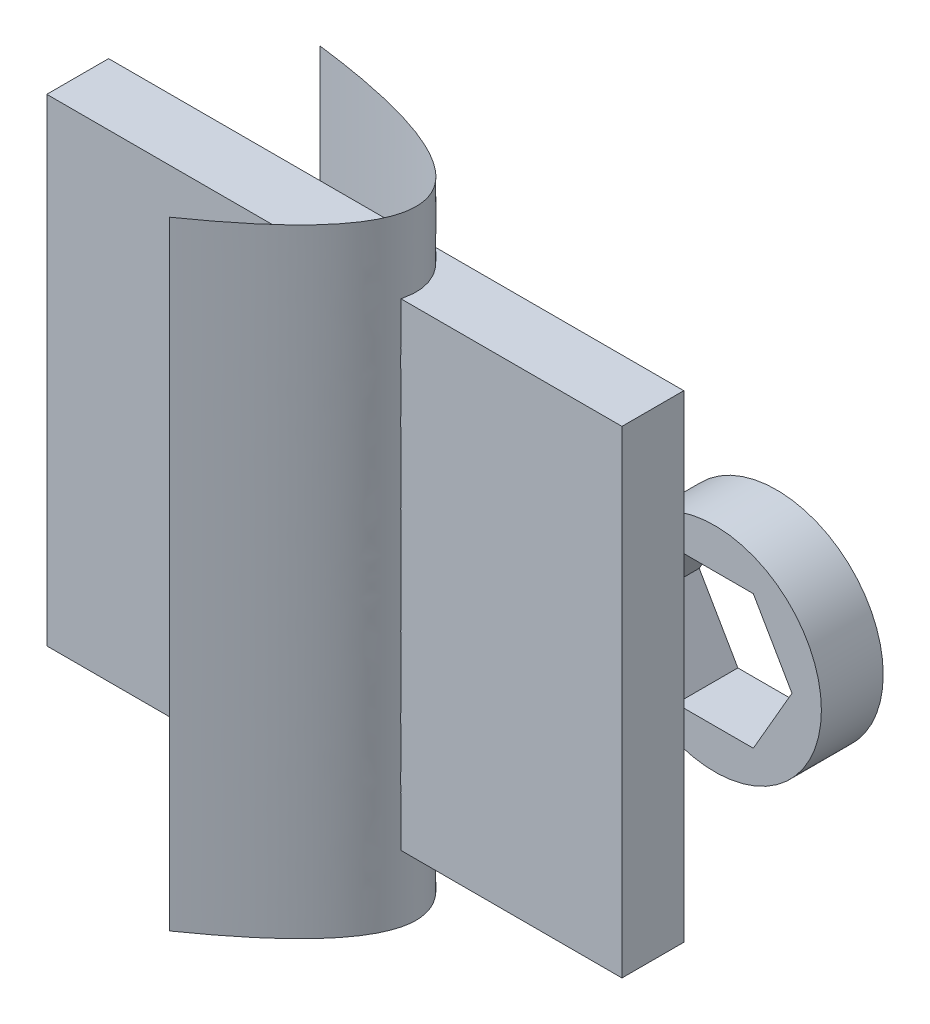
SolidWorks part; units mm, degrees
ref_plane "Спереди" through (0, 0, 0) normal (0, 0, 1) x (1, 0, 0)
ref_plane "Сверху" through (0, 0, 0) normal (0, 1, 0) x (1, 0, 0)
ref_plane "Справа" through (0, 0, 0) normal (1, 0, 0) x (0, 0, -1)
sketch "Эскиз1_fr" plane through (0, 0, 0) normal (0, 0, 1) x (1, 0, 0)
  line L1 (-48.994, 38.0205) -> (44.0482, 38.0205)
  line L2 (-48.994, 38.0205) -> (-48.994, -39.257)
  line L3 (-48.994, -39.257) -> (44.0482, -39.257)
  line L4 (44.0482, 38.0205) -> (44.0482, -39.257)
extrude "Бобышка-Вытянуть1" add sketch "Эскиз1_fr" along normal blind 10
ref_plane "Плоскость4" through (0, 0, -5) normal (0, 0, 1) x (1, 0, 0)
sketch "Эскиз5" plane through (0, 0, -5) normal (0, 0, 1) x (1, 0, 0)
  line L0 (44.0482, -39.257) -> (44.0482, 38.0205) construction
  circle A0 centre (44.0482, -0.6182) radius 17.2618
extrude "Бобышка-Вытянуть2" add sketch "Эскиз5" against normal blind 10 separate body
ref_plane "Плоскость5" through (0, 0, 20) normal (0, 0, 1) x (1, 0, 0)
sketch "Эскиз6" plane through (0, 0, 20) normal (0, 0, 1) x (1, 0, 0)
  line L0 (44.0482, -39.257) -> (44.0482, 38.0205) construction
  line L1 (50.2984, -11.4439) -> (56.5486, -0.6182)
  line L2 (56.5486, -0.6182) -> (50.2984, 10.2074)
  line L3 (50.2984, 10.2074) -> (37.798, 10.2074)
  line L4 (37.798, 10.2074) -> (31.5478, -0.6182)
  line L5 (31.5478, -0.6182) -> (37.798, -11.4439)
  line L6 (37.798, -11.4439) -> (50.2984, -11.4439)
  circle A0 centre (44.0482, -0.6182) radius 10.8257 construction
sketch "Эскиз7" plane through (0, 0, 0) normal (0, 1, 0) x (1, 0, 0)
  spline S0 degree 2 poles (-9.8895, -29.2716) (32.2081, 0.1563) (-21.677, 6.8901) knots 0 0 0 1 1 1
surface "Поверхность-Вытянуть1" sketch "Эскиз7" parameters "D1"=50, "D2"=50
split "Разделить1" trim tools "Эскиз6" bodies to split 105 resulting bodies 107
